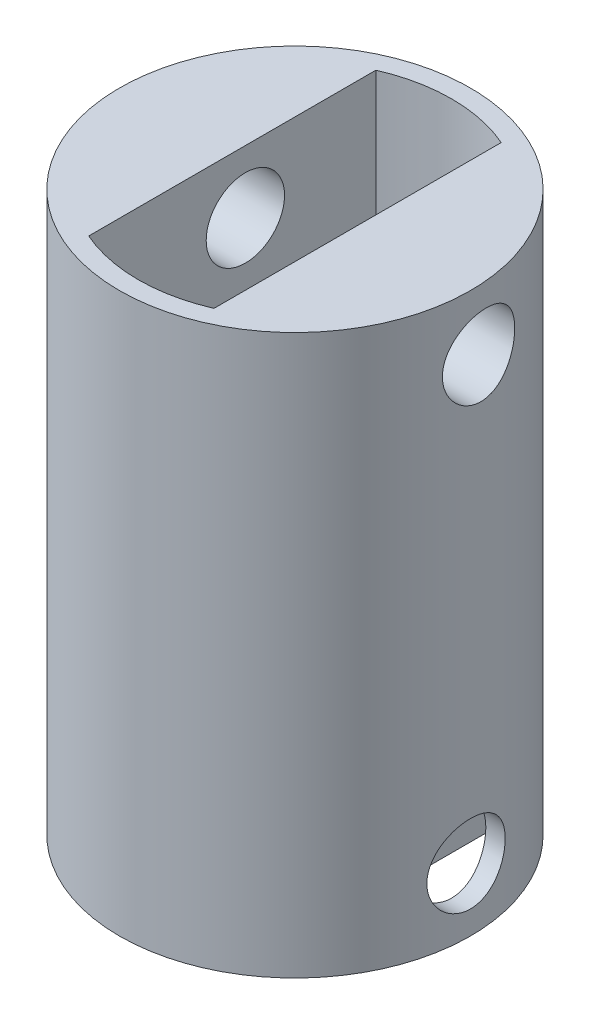
SolidWorks part; units mm, degrees
ref_plane "Front Plane" through (0, 0, 0) normal (0, 0, 1) x (1, 0, 0)
ref_plane "Top Plane" through (0, 0, 0) normal (0, 1, 0) x (1, 0, 0)
ref_plane "Right Plane" through (0, 0, 0) normal (1, 0, 0) x (0, 0, -1)
sketch "Sketch1" plane through (0, 0, 0) normal (0, 1, 0) x (1, 0, 0)
  circle A0 centre (0, 0) radius 14.224
  dimension "D1" = 28.448
extrude "Boss-Extrude1" add sketch "Sketch1" along normal blind 45.3136
sketch "Sketch2" plane through (0, 45.3136, 0) normal (0, 1, 0) x (1, 0, 0)
  line L0 (5.08, 11.6397) -> (5.08, -11.6397)
  line L1 (-5.08, 11.6397) -> (-5.08, -11.6397)
  arc A0 (-5.08, -11.6397) -> (5.08, -11.6397) centre (0, 0) ccw
  arc A1 (5.08, 11.6397) -> (-5.08, 11.6397) centre (0, 0) ccw
  dimension "D2" = 25.4
  dimension "D1" = 5.08
  dimension "D3" = 5.08
extrude "Cut-Extrude1" cut sketch "Sketch2" against normal blind 10.16
sketch "Sketch3" plane through (0, 0, 0) normal (0, -1, 0) x (1, 0, 0)
  line L0 (-2.54, 12.4434) -> (-2.54, -12.4434)
  line L1 (-7.62, 10.16) -> (-7.62, -10.16)
  line L2 (2.54, 12.4434) -> (2.54, -12.4434)
  line L3 (7.62, 10.16) -> (7.62, -10.16)
  arc A0 (-7.62, 10.16) -> (-7.62, -10.16) centre (0, 0) ccw
  arc A1 (-2.54, -12.4434) -> (2.54, -12.4434) centre (0, 0) ccw
  arc A2 (7.62, -10.16) -> (7.62, 10.16) centre (0, 0) ccw
  arc A3 (2.54, 12.4434) -> (-2.54, 12.4434) centre (0, 0) ccw
  dimension "D1" = 25.4
  dimension "D2" = 2.54
  dimension "D3" = 5.08
  dimension "D4" = 2.54
  dimension "D5" = 5.08
extrude "Cut-Extrude2" cut sketch "Sketch3" against normal blind 10.16
sketch "Sketch4" plane through (-5.08, 0, 0) normal (1, 0, 0) x (0, 0, -1)
  line L0 (14.224, 45.3136) -> (-14.224, 45.3136) construction
  line L5 (10.16, 0) -> (-10.16, 0) construction
  circle A0 centre (1.0603, 40.2336) radius 3.175
  circle A2 centre (0, 5.08) radius 3.175
  dimension "D1" = 6.35
  dimension "D3" = 6.35
  dimension "D2" = 5.08
  dimension "D4" = 5.08
extrude "Cut-Extrude3" cut sketch "Sketch4" against normal through all both and the other way through all
sketch "Sketch5" plane through (0, 35.1536, 0) normal (0, 1, 0) x (1, 0, 0)
  circle A0 centre (0, 0) radius 2.54
  dimension "D1" = 5.08
extrude "Cut-Extrude4" cut sketch "Sketch5" against normal through all
